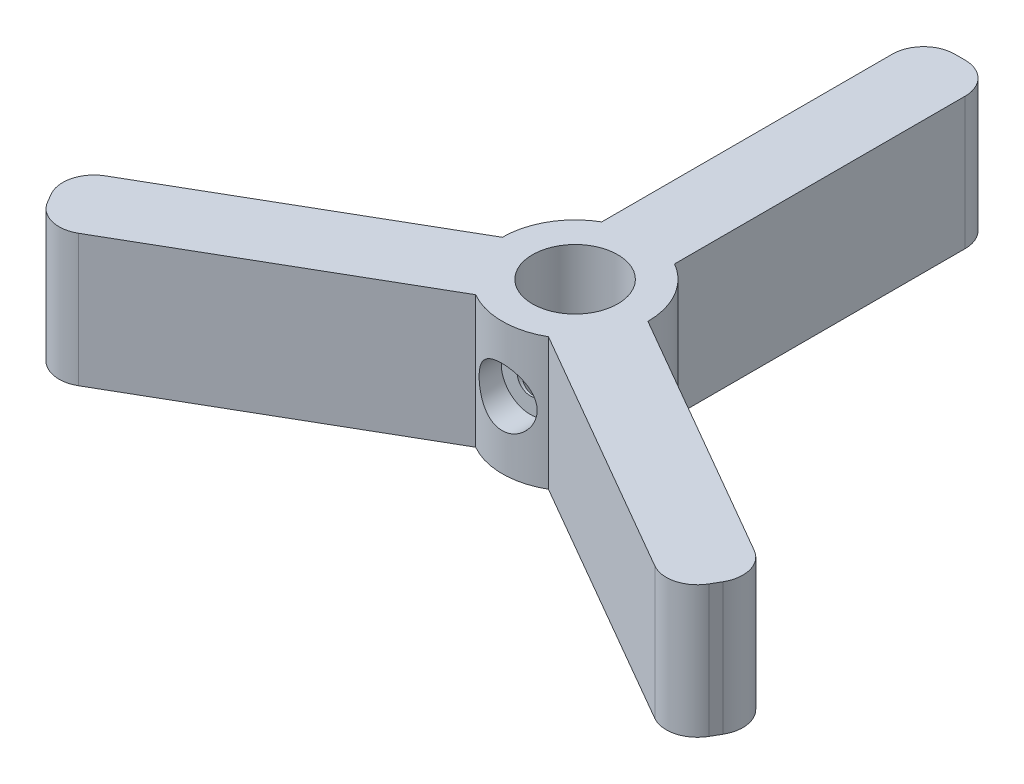
SolidWorks part; units mm, degrees
ref_plane "Front Plane" through (0, 0, 0) normal (0, 0, 1) x (1, 0, 0)
ref_plane "Top Plane" through (0, 0, 0) normal (0, 1, 0) x (1, 0, 0)
ref_plane "Right Plane" through (0, 0, 0) normal (1, 0, 0) x (0, 0, -1)
sketch "Sketch1" plane through (0, 0, 0) normal (0, 1, 0) x (1, 0, 0)
  line L0 (0, 0) -> (0, 37) construction
  line L1 (0, 0) -> (32.0429, -18.5) construction
  line L2 (0, 0) -> (-32.0429, -18.5) construction
  line L3 (-0.5, 37) -> (0.5, 37)
  line L4 (-32.2929, -18.067) -> (-31.7929, -18.933)
  line L5 (32.2929, -18.067) -> (31.7929, -18.933)
  line L6 (27.6949, -20.0311) -> (3.5, -6.0622)
  line L7 (-3.5, -6.0622) -> (-27.6949, -20.0311)
  line L8 (31.1949, -13.9689) -> (7, 0)
  line L9 (3.5, 6.0622) -> (3.5, 34)
  line L10 (-3.5, 34) -> (-3.5, 6.0622)
  line L11 (-7, 0) -> (-31.1949, -13.9689)
  arc A0 (31.7929, -18.933) -> (27.6949, -20.0311) centre (29.1949, -17.433) cw
  arc A1 (32.2929, -18.067) -> (31.1949, -13.9689) centre (29.6949, -16.567) ccw
  arc A2 (-32.2929, -18.067) -> (-31.1949, -13.9689) centre (-29.6949, -16.567) cw
  arc A3 (-31.7929, -18.933) -> (-27.6949, -20.0311) centre (-29.1949, -17.433) ccw
  arc A4 (-0.5, 37) -> (-3.5, 34) centre (-0.5, 34) ccw
  arc A5 (0.5, 37) -> (3.5, 34) centre (0.5, 34) cw
  arc A6 (-3.5, -6.0622) -> (3.5, -6.0622) centre (0, 0) ccw
  arc A7 (7, 0) -> (3.5, 6.0622) centre (0, 0) ccw
  arc A8 (-3.5, 6.0622) -> (-7, 0) centre (0, 0) ccw
  point P8 (0, 37)
  point P11 (-32.0429, -18.5)
  point P14 (32.0429, -18.5)
  point P21 (30.2929, -21.5311)
  point P24 (33.7929, -15.4689)
  point P27 (-33.7929, -15.4689)
  point P30 (-30.2929, -21.5311)
  point P33 (-3.5, 37)
  point P36 (3.5, 37)
  dimension "D13" = 3
  dimension "D14" = 14
  dimension "D1" = 120
  dimension "D2" = 120
  dimension "D3" = 37
  dimension "D4" = 37
  dimension "D5" = 37
  dimension "D6" = 7
  dimension "D7" = 90
  dimension "D8" = 7
  dimension "D9" = 90
  dimension "D10" = 7
  dimension "D11" = 120
  dimension "D12" = 120
  dimension "D15" = 27.9378
extrude "Boss-Extrude1" add sketch "Sketch1" along normal blind 12.7
sketch "Sketch2" plane through (0, 12.7, 0) normal (0, 1, 0) x (1, 0, 0)
  circle A0 centre (0, 0) radius 4.1
  dimension "D1" = 8.2
extrude "Cut-Extrude1" cut sketch "Sketch2" against normal through all
hole_wizard "CBORE for M5 Hex Head Bolt1" positions "3DSketch1" profile "Sketch4" counterbore size "M5" standard "ANSI Metric"
sketch3d "3DSketch1"
  line L0 (0, 12.7, 7) -> (0, 0, 7) construction
  line L2 (3.5, 6.35, 6.0622) -> (-3.5, 6.35, 6.0622) construction
  line L3 (3.5, 12.7, 6.0622) -> (3.5, 0, 6.0622) construction
  line L4 (-3.5, 12.7, 6.0622) -> (-3.5, 0, 6.0622) construction
  arc A0 (-3.5, 12.7, 6.0622) -> (3.5, 12.7, 6.0622) centre (0, 12.7, 0) ccw construction
  arc A1 (-3.5, 0, 6.0622) -> (3.5, 0, 6.0622) centre (0, 0, 0) ccw construction
  point P0 (-0.0229, 6.3898, 7)
  point P3 (1.3839, -4.6841, 0)
  point P9 (0, 19.7, 0)
  point P15 (0, 7, 0)
sketch "Sketch4" plane through (-0.0229, 6.3898, 7) normal (0, 1, 0) x (1, 0, 0.0033)
  line L0 (0, 0) -> (0, 18.7511)
  line L1 (0, 18.7511) -> (1.25, 18)
  line L2 (1.25, 18) -> (1.25, 2.7)
  line L3 (1.25, 2.7) -> (2.8, 2.7)
  line L4 (2.8, 2.7) -> (2.8, 0)
  line L5 (2.8, 0) -> (0, 0)
  line L10 (0, 18.7511) -> (-1.25, 18) construction
  line L11 (0, -6.35) -> (0, 107.95) construction
  dimension "Hole Dia." = 2.5
  dimension "Hole Depth" = 18
  dimension "C'Bore Dia." = 5.6
  dimension "C'Bore Depth" = 2.7
  dimension "Drill Angle" = 118
